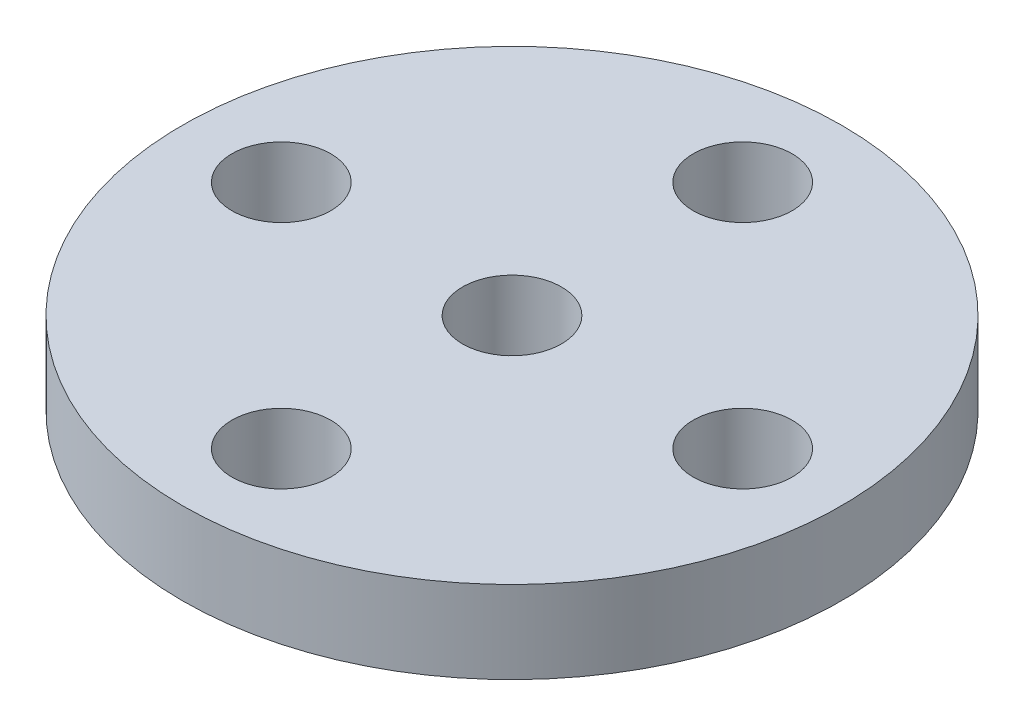
SolidWorks part; units mm, degrees
material "聚脂树脂"
ref_plane "前视基准面" through (0, 0, 0) normal (0, 0, 1) x (1, 0, 0)
ref_plane "上视基准面" through (0, 0, 0) normal (0, 1, 0) x (1, 0, 0)
ref_plane "右视基准面" through (0, 0, 0) normal (1, 0, 0) x (0, 0, -1)
other "Configuration Table"
sketch "草图1" plane through (0, 0, 0) normal (0, 1, 0) x (1, 0, 0)
  line L0 (0, 0) -> (0, 14.6276) construction
  line L1 (0, 0) -> (20.1674, 0) construction
  circle A0 centre (0, 0) radius 10
  circle A1 centre (0, 7) radius 1.5
  circle A2 centre (7, 0) radius 1.5
  circle A3 centre (0, 0) radius 1.5
  circle A4 centre (0, -7) radius 1.5
  circle A5 centre (-7, 0) radius 1.5
  dimension "D1" = 20
  dimension "D2" = 3
  dimension "D3" = 3
  dimension "D4" = 7
  dimension "D5" = 7
  dimension "D6" = 3
extrude "凸台-拉伸1" add sketch "草图1" along normal blind 2.5
